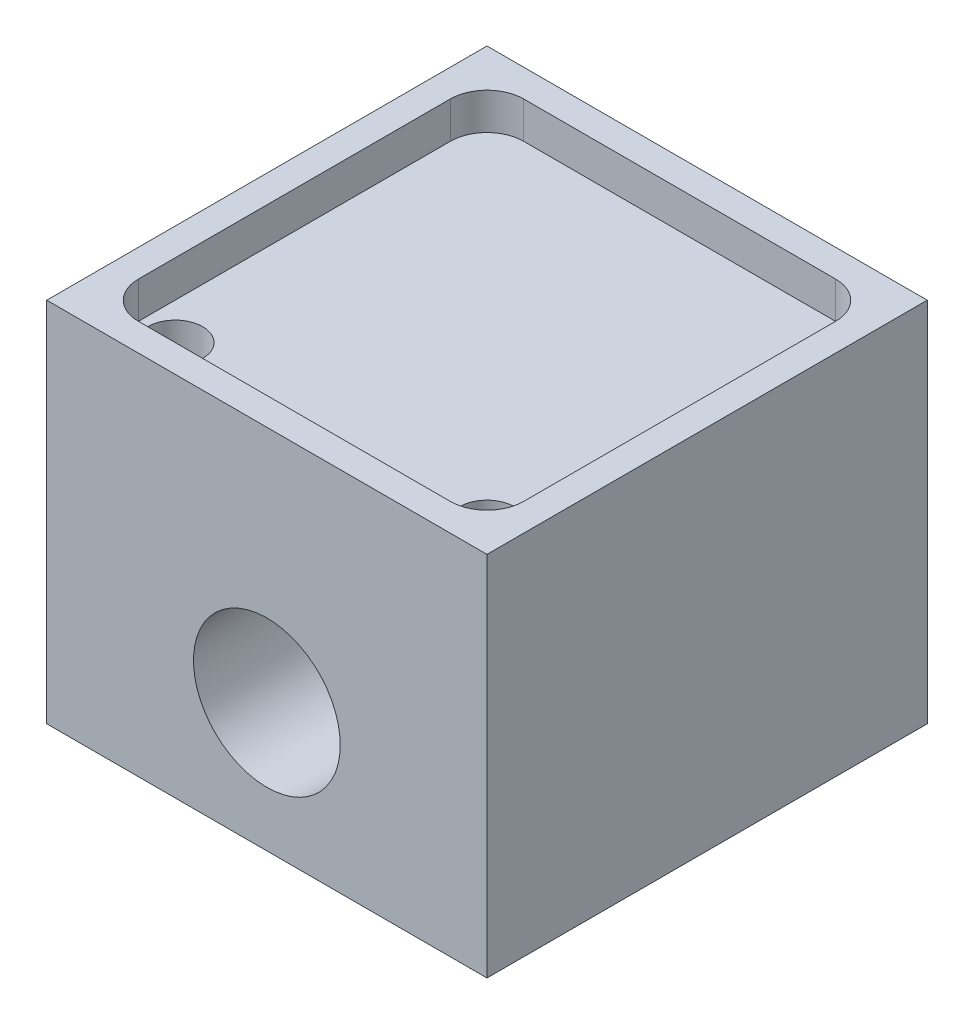
SolidWorks part; units mm, degrees
ref_plane "Front Plane" through (0, 0, 0) normal (0, 0, 1) x (1, 0, 0)
ref_plane "Top Plane" through (0, 0, 0) normal (0, 1, 0) x (1, 0, 0)
ref_plane "Right Plane" through (0, 0, 0) normal (1, 0, 0) x (0, 0, -1)
sketch "Sketch1" plane through (0, 0, 0) normal (0, 1, 0) x (1, 0, 0)
  line L1 (-12, 12) -> (12, 12)
  line L2 (-12, 12) -> (-12, -12)
  line L3 (-12, -12) -> (12, -12)
  line L4 (12, 12) -> (12, -12)
  line L5 (-12, 12) -> (12, -12) construction
  line L6 (-12, -12) -> (12, 12) construction
  point P0 (0, 0)
  dimension "D1" = 24
  dimension "D2" = 24
extrude "Boss-Extrude1" add sketch "Sketch1" along normal blind 20
sketch "Sketch2" plane through (0, 20, 0) normal (0, 1, 0) x (1, 0, 0)
  line L1 (-10.5, 10.5) -> (10.5, 10.5)
  line L2 (-10.5, 10.5) -> (-10.5, -10.5)
  line L3 (-10.5, -10.5) -> (10.5, -10.5)
  line L4 (10.5, 10.5) -> (10.5, -10.5)
  line L5 (-10.5, 10.5) -> (10.5, -10.5) construction
  line L6 (-10.5, -10.5) -> (10.5, 10.5) construction
  point P0 (0, 0)
  dimension "D1" = 21
  dimension "D2" = 21
extrude "Cut-Extrude1" cut sketch "Sketch2" against normal blind 2
fillet "Fillet2" radius 2 4 edges at (10.5, 19, -10.5) (-10.5, 19, -10.5) (-10.5, 19, 10.5) (10.5, 19, 10.5)
sketch "Sketch3" plane through (0, 0, 12) normal (0, 0, 1) x (1, 0, 0)
  line L0 (0, 0) -> (0, 7) construction
  line L1 (0, 0) -> (0, 20) construction
  line L2 (-12, 20) -> (12, 20) construction
  circle A0 centre (0, 7) radius 4
  dimension "D2" = 8
  dimension "D1" = 7
extrude "Cut-Extrude2" cut sketch "Sketch3" against normal blind 42
sketch "Sketch5" plane through (0, 18, 0) normal (0, 1, 0) x (1, 0, 0)
  line L0 (0, 0) -> (0, -12) construction
  line L1 (-12, -12) -> (12, -12) construction
  circle A0 centre (-8.5, -8.5) radius 1.5
  circle A1 centre (8.5, -8.5) radius 1.5
  dimension "D1" = 3
extrude "Cut-Extrude3" cut sketch "Sketch5" against normal blind 42
